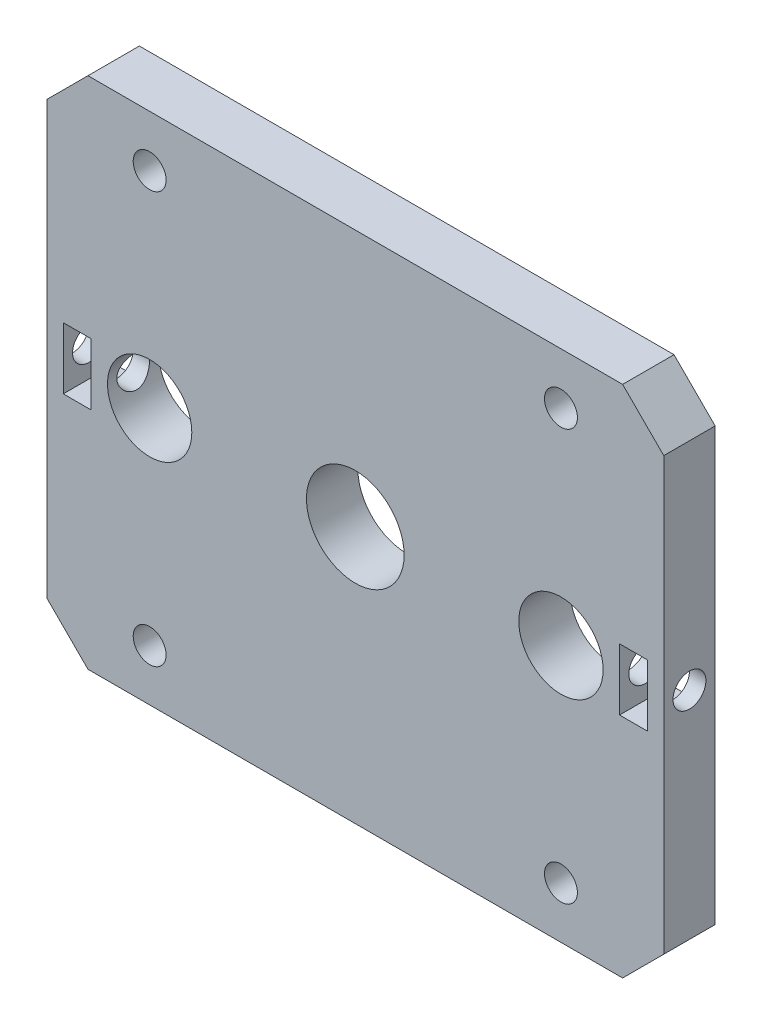
SolidWorks part; units mm, degrees
ref_plane "前视基准面" through (0, 0, 0) normal (0, 0, 1) x (1, 0, 0)
ref_plane "上视基准面" through (0, 0, 0) normal (0, 1, 0) x (1, 0, 0)
ref_plane "右视基准面" through (0, 0, 0) normal (1, 0, 0) x (0, 0, -1)
other "Configuration Table"
sketch "草图1" plane through (0, 0, 0) normal (0, 0, 1) x (1, 0, 0)
  line L1 (-30, -25) -> (30, -25)
  line L2 (-30, -25) -> (-30, 25)
  line L3 (-30, 25) -> (30, 25)
  line L4 (30, -25) -> (30, 25)
  line L5 (-30, -25) -> (30, 25) construction
  line L6 (-30, 25) -> (30, -25) construction
  point P0 (0, 0)
  dimension "D1" = 50
  dimension "D2" = 60
extrude "凸台-拉伸1" add sketch "草图1" along normal blind 5
hole_wizard "孔1" positions "草图2" profile "草图3" legacy
sketch "草图2" plane through (0, 0, 5) normal (0, 0, 1) x (1, 0, 0)
  point P0 (0, 0)
sketch "草图3" plane through (0, 0, 5) normal (1, 0, 0) x (0, -1, 0)
  line L0 (0, 0) -> (0, 20)
  line L1 (0, 20) -> (4.75, 20)
  line L2 (4.75, 20) -> (4.75, 0)
  line L3 (4.75, 0) -> (0, 0)
  line L4 (0, 110) -> (0, -10) construction
  dimension "直径" = 9.5
  dimension "深度" = 20
sketch "草图9" plane through (0, 0, 5) normal (0, 0, 1) x (1, 0, 0)
  circle A0 centre (0, 18.25) radius 2.5
  circle A1 centre (0, -18.25) radius 2.5
  dimension "D1" = 5
  dimension "D2" = 5
  dimension "D3" = 18.25
  dimension "D4" = 18.25
sketch "草图15" plane through (0, 0, 5) normal (0, 0, 1) x (1, 0, 0)
  line L0 (-30, 0) -> (30, 0)
  line L1 (-30, 25) -> (-30, -25) construction
  line L2 (30, -25) -> (30, 25) construction
  line L3 (0, 25) -> (0, -25)
  line L4 (30, 25) -> (-30, 25) construction
  line L5 (-30, -25) -> (30, -25) construction
  line L6 (0, 0) -> (-29.5019, 29.5019)
  line L8 (30, 14.0027) -> (14.0027, 14.0027)
  line L9 (-30, 25) -> (-14.0027, 25)
  line L10 (-30, 25) -> (-30, 14.0027)
  line L11 (-30, 14.0027) -> (-14.0027, 14.0027)
  line L12 (-14.0027, 25) -> (-14.0027, 14.0027)
  line L13 (14.0027, 25) -> (14.0027, 14.0027)
  line L14 (30, 25) -> (14.0027, 25)
  line L15 (30, 25) -> (30, 14.0027)
  line L16 (-30, -14.0027) -> (-14.0027, -14.0027)
  line L17 (-14.0027, -25) -> (-14.0027, -14.0027)
  line L18 (-30, -25) -> (-14.0027, -25)
  line L19 (-30, -25) -> (-30, -14.0027)
  line L20 (30, -25) -> (30, -14.0027)
  line L21 (30, -25) -> (14.0027, -25)
  line L22 (14.0027, -25) -> (14.0027, -14.0027)
  line L23 (30, -14.0027) -> (14.0027, -14.0027)
  circle A0 centre (-20, 20) radius 1.6
  circle A1 centre (20, 20) radius 1.6
  circle A2 centre (20, -20) radius 1.6
  circle A3 centre (-20, -20) radius 1.6
  dimension "D3" = 3.2
  dimension "D1" = 45
  dimension "D2" = 40
chamfer "倒角1" distance 4 angle 45 4 edges at (30, -25, 2.5) (-30, -25, 2.5) (-30, 25, 2.5) (30, 25, 2.5)
extrude "切除-拉伸1" cut sketch "草图15" against normal through all contours L6 A0 | L6 A0 | A1 | A2 | A3
hole_wizard "孔2" positions "草图16" profile "草图17" legacy end condition through all
sketch "草图16" plane through (0, 0, 5) normal (0, 0, 1) x (1, 0, 0)
  line L0 (0, 0) -> (-30, 0) construction
  line L1 (-30, 21) -> (-30, -21) construction
  line L3 (0, 0) -> (30, 0) construction
  line L4 (30, -21) -> (30, 21) construction
  point P0 (-20, 0)
  point P2 (20, 0)
  point P20 (19.7318, 0)
  dimension "D1" = 20
  dimension "D2" = 20
sketch "草图17" plane through (-20, 0, 5) normal (1, 0, 0) x (0, -1, 0)
  line L0 (0, 0) -> (0, 5)
  line L1 (0, 5) -> (4.1, 5)
  line L2 (4.1, 5) -> (4.1, 0)
  line L3 (4.1, 0) -> (0, 0)
  line L4 (0, 110) -> (0, -10) construction
  dimension "直径" = 8.2
  dimension "深度" = 5
sketch "草图19" plane through (0, 0, 5) normal (0, 0, 1) x (1, 0, 0)
  line L0 (24.1, 0) -> (30, 0) construction
  line L1 (30, -21) -> (30, 21) construction
  line L3 (25.7, -3) -> (28.4, -3)
  line L4 (25.7, -3) -> (25.7, 3)
  line L5 (25.7, 3) -> (28.4, 3)
  line L6 (28.4, -3) -> (28.4, 3)
  line L7 (25.7, -3) -> (28.4, 3) construction
  line L8 (25.7, 3) -> (28.4, -3) construction
  circle A0 centre (20, 0) radius 4.1 construction
  point P6 (27.05, 0)
  dimension "D1" = 6
  dimension "D2" = 2.7
extrude "切除-拉伸2" cut sketch "草图19" against normal blind 10
hole_wizard "孔3" positions "草图21" profile "草图22" legacy
sketch "草图21" plane through (30, 0, 0) normal (1, 0, 0) x (0, 0, -1)
  line L0 (-5, 0) -> (0, 0) construction
  line L1 (-5, -21) -> (-5, 21) construction
  point P0 (-2.5, 0)
  point P10 (-2.5, 0)
sketch "草图22" plane through (30, 0, 2.5) normal (0, 1, 0) x (0, 0, -1)
  line L0 (0, 0) -> (0, 10)
  line L1 (0, 10) -> (1.6, 10)
  line L2 (1.6, 10) -> (1.6, 0)
  line L3 (1.6, 0) -> (0, 0)
  line L4 (0, 110) -> (0, -10) construction
  dimension "直径" = 3.2
  dimension "深度" = 10
ref_plane "基准面1" through (0, 0, 0) normal (1, 0, 0) x (0, 0, -1)
mirror "镜向1" about plane through (0, 0, 0) normal (1, 0, 0) of "切除-拉伸2", "孔3"
